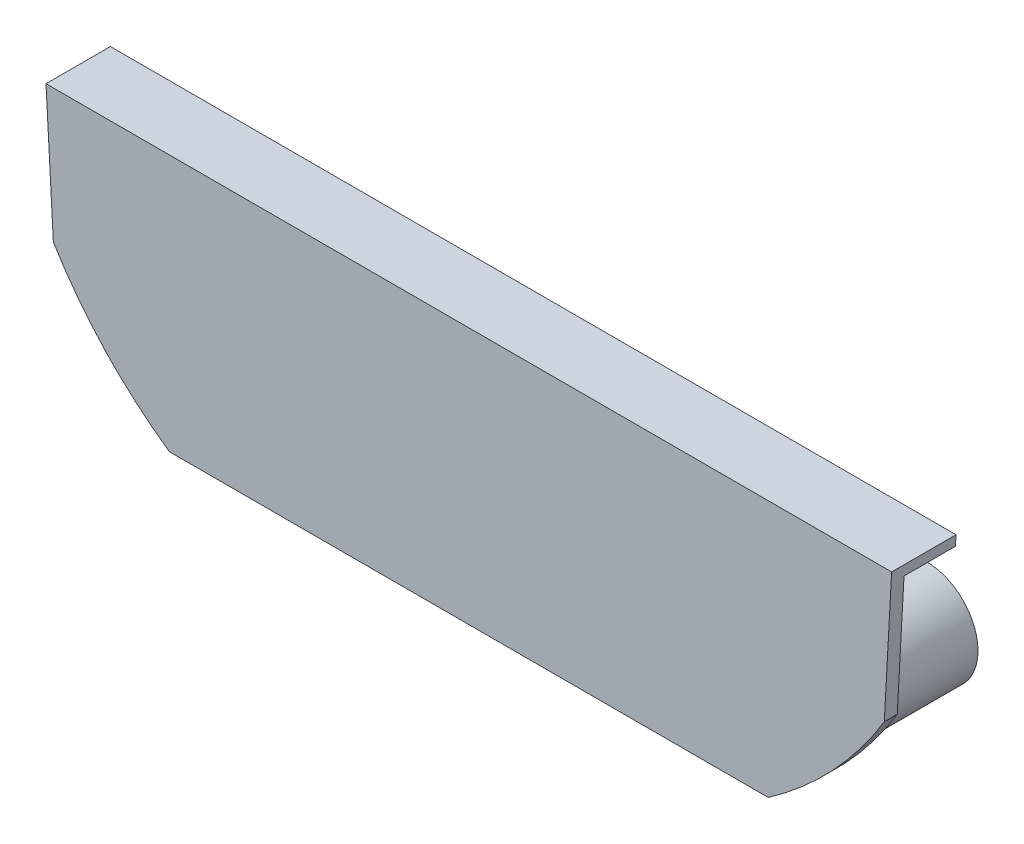
SolidWorks part; units mm, degrees
ref_plane "Plano frontal" through (0, 0, 0) normal (0, 0, 1) x (1, 0, 0)
ref_plane "Plano superior" through (0, 0, 0) normal (0, 1, 0) x (1, 0, 0)
ref_plane "Plano direito" through (0, 0, 0) normal (1, 0, 0) x (0, 0, -1)
sketch "Esboço1" plane through (0, 0, 0) normal (0, 0, 1) x (1, 0, 0)
  line L0 (29.125, 25) -> (29.125, 0) construction
  line L1 (0, 0) -> (58.25, 0)
  line L2 (-12, 25) -> (-11.2852, 12.0197)
  line L3 (-12, 25) -> (70.25, 25)
  line L4 (70.25, 25) -> (69.5352, 12.0197)
  arc A0 (-11.2852, 12.0197) -> (0, 0) centre (22.8926, 32.8013) ccw
  arc A1 (69.5352, 12.0197) -> (58.25, 0) centre (35.3574, 32.8013) cw
  point P9 (-11.6426, 18.5098)
  point P14 (69.8926, 18.5098)
  dimension "D1" = 25
  dimension "D4" = 12
  dimension "D3" = 13
  dimension "D5" = 40
  dimension "D2" = 41.125
  dimension "D6" = 11.2852
extrude "Ressalto-extrusão1" add sketch "Esboço1" along normal blind 1.26
sketch "Esboço2" plane through (0, 0, 1.26) normal (0, 0, 1) x (1, 0, 0)
  line L0 (-12, 25) -> (4.19, 25)
  line L1 (70.25, 25) -> (-12, 25) construction
  line L2 (0, 0) -> (58.25, 0) construction
  line L3 (-3.61, 11.3) -> (62.39, 11.3)
  circle A0 centre (-3.61, 11.3) radius 5
  circle A1 centre (62.39, 11.3) radius 5
  dimension "D2" = 10
  dimension "D5" = 10
  dimension "D1" = 16.19
  dimension "D3" = 11.3
  dimension "D4" = 7.8
  dimension "D6" = 66
extrude "Ressalto-extrusão2" add sketch "Esboço2" against normal blind 11.26
sketch "Esboço3" plane through (0, 0, 0) normal (0, 0, -1) x (-1, 0, 0)
  line L0 (-70.25, 25) -> (12, 25)
  line L1 (12, 25) -> (11.9449, 24)
  line L2 (12, 25) -> (11.2852, 12.0197) construction
  line L3 (11.9449, 24) -> (-70.1949, 24)
  line L4 (-69.5352, 12.0197) -> (-70.25, 25) construction
  line L5 (-70.1949, 24) -> (-70.25, 25)
  dimension "D1" = 1
extrude "Ressalto-extrusão3" add sketch "Esboço3" along normal blind 5
